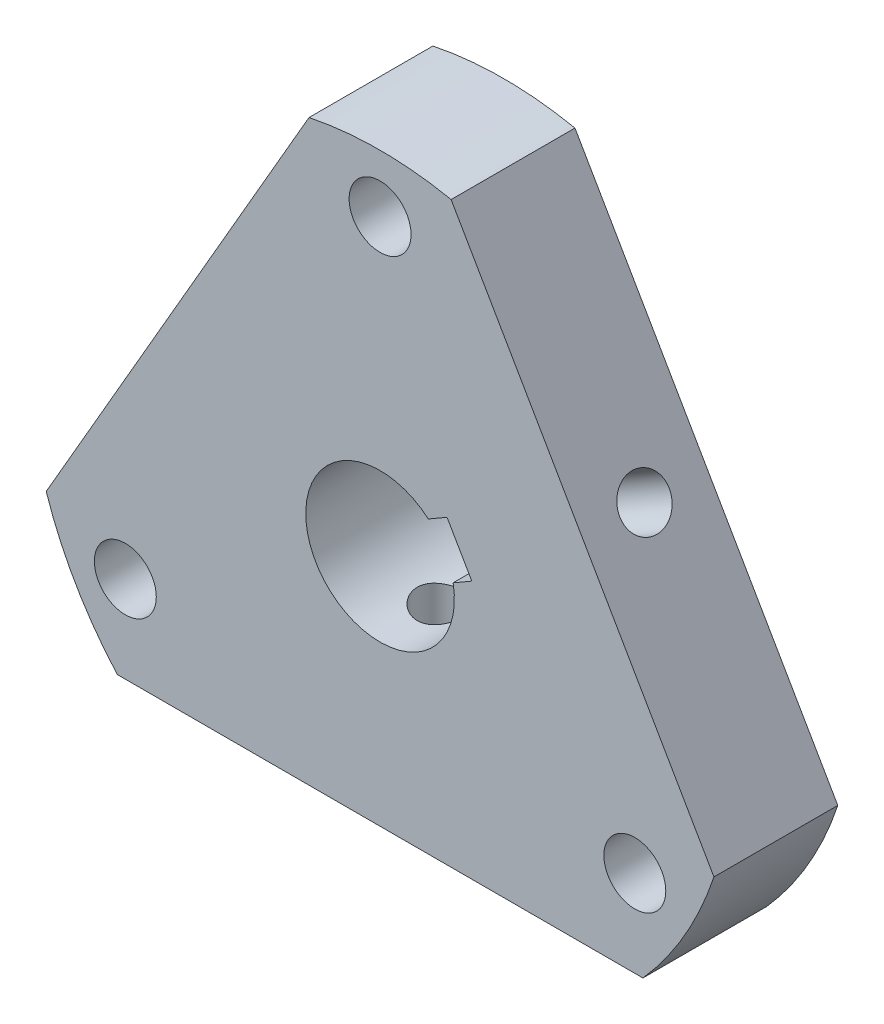
SolidWorks part; units mm, degrees
ref_plane "正面" through (0, 0, 0) normal (0, 0, 1) x (1, 0, 0)
ref_plane "平面" through (0, 0, 0) normal (0, 1, 0) x (1, 0, 0)
ref_plane "右側面" through (0, 0, 0) normal (1, 0, 0) x (0, 0, -1)
sketch "ｽｹｯﾁ1" plane through (0, 0, 0) normal (0, 0, 1) x (1, 0, 0)
  line L0 (0, 0) -> (16.3462, 9.4375) construction
  line L1 (0, 37.75) -> (-32.6925, -18.875)
  line L2 (-32.6925, -18.875) -> (32.6925, -18.875)
  line L3 (32.6925, -18.875) -> (0, 37.75)
  line L4 (1.8701, 3.3891) -> (5.4086, 5.4321)
  line L5 (1.8701, 3.3891) -> (3.8701, -0.075)
  line L6 (5.4086, 5.4321) -> (7.4086, 1.9679)
  line L7 (3.8701, -0.075) -> (7.4086, 1.9679)
  line L8 (1.8701, 3.3891) -> (7.4086, 1.9679) construction
  line L9 (5.4086, 5.4321) -> (3.8701, -0.075) construction
  circle A0 centre (0, 23.75) radius 2.5
  circle A1 centre (20.5681, -11.875) radius 2.5
  circle A2 centre (-20.5681, -11.875) radius 2.5
  circle A3 centre (0, 0) radius 6
  circle A4 centre (0, 0) radius 28.4
  circle A5 centre (0, 0) radius 18.875 construction
  point P9 (0, 0)
  point P17 (4.6393, 2.6785)
  dimension "D1" = 5
  dimension "D2" = 23.75
  dimension "D4" = 12
  dimension "D5" = 56.8
  dimension "D6" = 14
  dimension "D7" = 4
  dimension "D8" = 0
  dimension "D9" = 7.4
  dimension "D3" = 3
extrude "ﾎﾞｽ - 押し出し1" add sketch "ｽｹｯﾁ1" along normal blind 10 contours L3 A4 L1 L2 A3 A2 A1 A0
sketch "ｽｹｯﾁ2" plane through (16.3462, 9.4375, 0) normal (0.866, 0.5, 0) x (0, 0, -1)
  line L0 (0, -21.2201) -> (0, 21.2201) construction
  circle A0 centre (-5, 0) radius 2
  dimension "D1" = 5
  dimension "D2" = 4
extrude "ｶｯﾄ - 押し出し1" cut sketch "ｽｹｯﾁ2" against normal blind 15
sketch "ｽｹｯﾁ3" plane through (0, -18.875, 0) normal (0, -1, 0) x (1, 0, 0)
  line L0 (-21.2201, 10) -> (21.2201, 10) construction
  circle A0 centre (0, 5) radius 2
  dimension "D1" = 5
  dimension "D2" = 4
extrude "ｶｯﾄ - 押し出し2" cut sketch "ｽｹｯﾁ3" against normal blind 15
